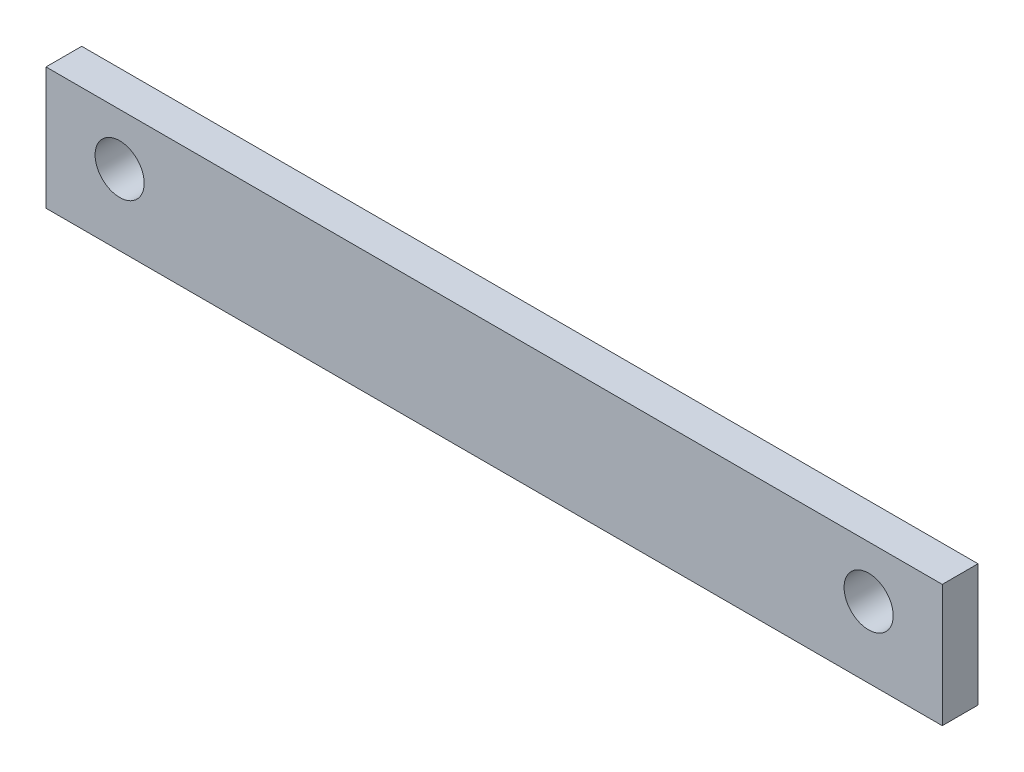
SolidWorks part; units mm, degrees
ref_plane "Front Plane" through (0, 0, 0) normal (0, 0, 1) x (1, 0, 0)
ref_plane "Top Plane" through (0, 0, 0) normal (0, 1, 0) x (1, 0, 0)
ref_plane "Right Plane" through (0, 0, 0) normal (1, 0, 0) x (0, 0, -1)
sketch "Sketch1" plane through (0, 0, 0) normal (0, 0, 1) x (1, 0, 0)
  line L0 (0, 0) -> (-16.8271, 10.8097)
  line L1 (0, 0) -> (0, 16.5927) construction
  line L2 (24.0722, 16.5927) -> (-24.0722, 16.5927)
  line L3 (-25.0722, 15.5927) -> (-25.0722, 8.4955)
  line L4 (-24.6327, 7.6673) -> (-1.121, -8.2449)
  line L5 (24.6327, 7.6673) -> (1.121, -8.2449)
  line L6 (25.0722, 15.5927) -> (25.0722, 8.4955)
  circle A0 centre (0, 0) radius 2.75
  circle A1 centre (-16.8271, 10.8097) radius 2.75
  circle A2 centre (16.8271, 10.8097) radius 2.75
  arc A3 (24.0722, 16.5927) -> (25.0722, 15.5927) centre (24.0722, 15.5927) cw
  arc A4 (24.6327, 7.6673) -> (25.0722, 8.4955) centre (24.0722, 8.4955) ccw
  arc A5 (-25.0722, 8.4955) -> (-24.6327, 7.6673) centre (-24.0722, 8.4955) ccw
  arc A6 (-25.0722, 15.5927) -> (-24.0722, 16.5927) centre (-24.0722, 15.5927) cw
  arc A7 (-1.121, -8.2449) -> (1.121, -8.2449) centre (0, -6.5886) ccw
  point P15 (25.0722, 16.5927)
  point P18 (25.0722, 7.9647)
  point P21 (-25.0722, 7.9647)
  point P24 (-25.0722, 16.5927)
  point P27 (0, -9.0036)
  dimension "D1" = 5.5
  dimension "D3" = 1
  dimension "D4" = 2
  dimension "D2" = 20
extrude "Boss-Extrude1" add sketch "Sketch1" along normal blind 4
sketch "Sketch2" plane through (0, 0, 4) normal (0, 0, 1) x (1, 0, 0)
  line L0 (-24.6327, 7.6673) -> (24.6327, 7.6673)
  line L1 (24.6327, 7.6673) -> (0.256, -10.0532)
  line L2 (0.256, -10.0532) -> (-24.6327, 7.6673)
extrude "Cut-Extrude1" cut sketch "Sketch2" against normal blind 10
sketch "Sketch3" plane through (0, 0, 4) normal (0, 0, 1) x (1, 0, 0)
  line L0 (-16.8271, 10.8097) -> (16.8271, 10.8097)
  line L1 (-25.0722, 16.5927) -> (-25.0722, 15.5927)
  line L2 (-25.0722, 16.5927) -> (-24.0722, 16.5927)
  line L3 (75.2677, 16.5927) -> (75.2677, 2.8875)
  line L4 (-25.0722, 16.5927) -> (75.2677, 16.5927)
  line L5 (-25.0722, 16.5927) -> (-25.0722, 2.8875)
  line L6 (-25.0722, 2.8875) -> (75.2677, 2.8875)
  line L7 (25.0977, 16.5927) -> (25.0977, 2.8875)
  circle A0 centre (-16.8271, 10.8097) radius 2.75
  circle A1 centre (67.0226, 10.8097) radius 2.75
extrude "Boss-Extrude3" add sketch "Sketch3" against normal blind 4
sketch "Sketch4" plane through (0, 0, 4) normal (0, 0, 1) x (1, 0, 0)
  circle A0 centre (16.8271, 10.8097) radius 2.75
extrude "Boss-Extrude4" add sketch "Sketch4" against normal blind 4
